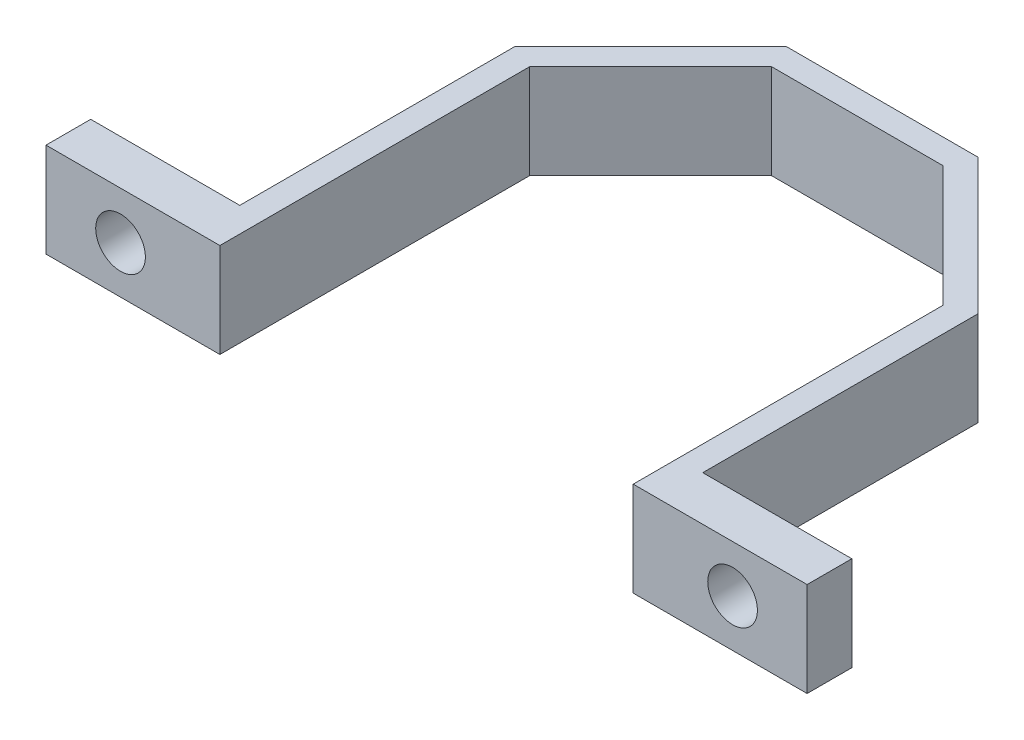
SolidWorks part; units mm, degrees
ref_plane "Front Plane" through (0, 0, 0) normal (0, 0, 1) x (1, 0, 0)
ref_plane "Top Plane" through (0, 0, 0) normal (0, 1, 0) x (1, 0, 0)
ref_plane "Right Plane" through (0, 0, 0) normal (1, 0, 0) x (0, 0, -1)
sketch "Sketch2" plane through (0, 0, 0) normal (0, 1, 0) x (1, 0, 0)
  line L0 (-9.6502, 23.2975) -> (-23.2975, 9.6502)
  line L1 (-20.7975, -12.1502) -> (-20.7975, -8.6146)
  line L2 (20.7975, -8.6146) -> (20.7975, 8.6146)
  line L3 (20.7975, 8.6146) -> (8.6146, 20.7975)
  line L4 (8.6146, 20.7975) -> (-8.6146, 20.7975)
  line L5 (-8.6146, 20.7975) -> (-20.7975, 8.6146)
  line L6 (-20.7975, 8.6146) -> (-20.7975, -8.6146)
  line L7 (20.7975, -12.1502) -> (20.7975, -8.6146)
  line L9 (-23.2975, 9.6502) -> (-23.2975, -9.6502)
  line L13 (23.2975, -9.6502) -> (23.2975, 9.6502)
  line L14 (23.2975, 9.6502) -> (9.6502, 23.2975)
  line L15 (9.6502, 23.2975) -> (-9.6502, 23.2975)
  line L16 (-23.2975, -9.6502) -> (-23.2975, -18.0475)
  line L17 (-23.2975, -22.5475) -> (-38.2975, -22.5475)
  line L18 (-38.2975, -22.5475) -> (-38.2975, -18.0475)
  line L19 (-38.2975, -18.0475) -> (-23.2975, -18.0475)
  line L20 (-20.7975, -12.1502) -> (-20.7975, -22.5475)
  line L21 (-20.7975, -22.5475) -> (-23.2975, -22.5475)
  line L22 (-23.2975, -9.6502) -> (-9.6502, -23.2975) construction
  line L24 (20.7975, -22.5475) -> (23.2975, -22.5475)
  line L25 (38.2975, -18.0475) -> (23.2975, -18.0475)
  line L26 (38.2975, -22.5475) -> (38.2975, -18.0475)
  line L27 (23.2975, -22.5475) -> (38.2975, -22.5475)
  line L28 (20.7975, -12.1502) -> (20.7975, -22.5475)
  line L29 (23.2975, -9.6502) -> (23.2975, -18.0475)
  line L30 (9.6502, -23.2975) -> (23.2975, -9.6502) construction
  line L31 (-20.7975, -8.6146) -> (-8.6146, -20.7975) [skipped]
  line L32 (-20.7975, -8.6146) -> (-8.6146, -20.7975) construction
  line L33 (-9.6502, -23.2975) -> (9.6502, -23.2975) construction
  line L34 (-8.6146, -20.7975) -> (8.6146, -20.7975) [skipped]
  line L35 (-8.6146, -20.7975) -> (8.6146, -20.7975) construction
  line L36 (8.6146, -20.7975) -> (20.7975, -8.6146) [skipped]
  line L37 (8.6146, -20.7975) -> (20.7975, -8.6146) construction
  circle A0 centre (0, 0) radius 20.7975 construction
  dimension "D1" = 2.5
extrude "Boss-Extrude1" add sketch "Sketch2" along normal blind 9.5
sketch "Sketch3" plane through (0, 0, 18.0475) normal (0, 0, -1) x (-1, 0, 0)
  circle A0 centre (30.7975, 4.75) radius 2.5
  circle A1 centre (-30.7975, 4.75) radius 2.5
extrude "Cut-Extrude1" cut sketch "Sketch3" against normal blind 9.5
